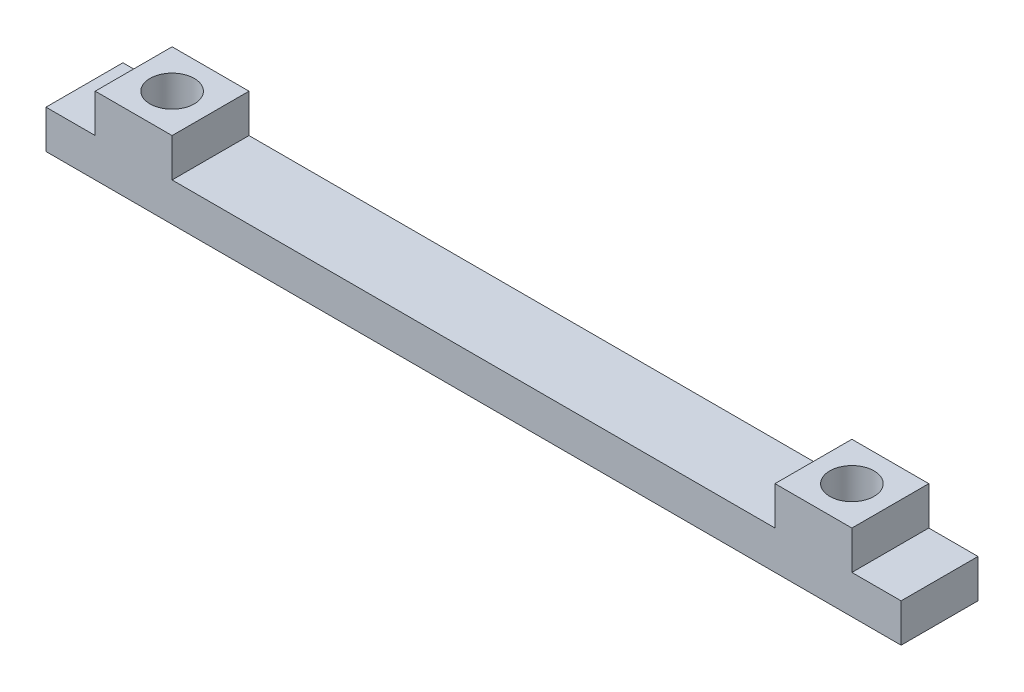
SolidWorks part; units mm, degrees
material "Alloy Steel"
ref_plane "Front Plane" through (0, 0, 0) normal (0, 0, 1) x (1, 0, 0)
ref_plane "Top Plane" through (0, 0, 0) normal (0, 1, 0) x (1, 0, 0)
ref_plane "Right Plane" through (0, 0, 0) normal (1, 0, 0) x (0, 0, -1)
sketch "Sketch1" plane through (0, 0, 0) normal (0, 0, 1) x (1, 0, 0)
  line L0 (35.306, 0) -> (35.306, 3.175) construction
  line L1 (0, 0) -> (70.612, 0)
  line L2 (0, 0) -> (0, 3.175)
  line L3 (0, 3.175) -> (70.612, 3.175)
  line L4 (70.612, 0) -> (70.612, 3.175)
  line L5 (4.064, 3.175) -> (10.414, 3.175)
  line L6 (4.064, 3.175) -> (4.064, 6.35)
  line L7 (4.064, 6.35) -> (10.414, 6.35)
  line L8 (10.414, 3.175) -> (10.414, 6.35)
  line L9 (60.198, 3.175) -> (66.548, 3.175)
  line L10 (60.198, 3.175) -> (60.198, 6.35)
  line L11 (60.198, 6.35) -> (66.548, 6.35)
  line L12 (66.548, 3.175) -> (66.548, 6.35)
  dimension "D1" = 4.064
  dimension "D2" = 3.175
  dimension "D4" = 49.784
  dimension "D5" = 3.175
  dimension "D6" = 6.35
extrude "Boss-Extrude1" add sketch "Sketch1" along normal blind 6.35 contours L1 L0 L3 L2 | L3 L8 L7 L6 | L3 L12 L11 L10 | L0 L1 L4 L3
sketch "Sketch2" plane through (0, 0, 0) normal (0, -1, 0) x (1, 0, 0)
  line L0 (70.612, 3.175) -> (0, 3.175) construction
  line L1 (70.612, 6.35) -> (70.612, 0) construction
  line L2 (0, 6.35) -> (0, 0) construction
  line L3 (7.239, 6.35) -> (7.239, 0) construction
  line L4 (63.373, 6.35) -> (63.373, 0) construction
  line L7 (4.064, 0) -> (10.414, 0)
  line L8 (4.064, 6.35) -> (4.064, 0)
  line L9 (10.414, 6.35) -> (4.064, 6.35)
  line L10 (10.414, 0) -> (10.414, 6.35)
  line L11 (4.064, 0) -> (10.414, 0)
  line L12 (4.064, 6.35) -> (4.064, 0)
  line L13 (10.414, 6.35) -> (4.064, 6.35)
  line L14 (10.414, 0) -> (10.414, 6.35)
  line L15 (60.198, 0) -> (66.548, 0)
  line L16 (60.198, 6.35) -> (60.198, 0)
  line L17 (66.548, 6.35) -> (60.198, 6.35)
  line L18 (66.548, 0) -> (66.548, 6.35)
  line L19 (60.198, 0) -> (66.548, 0)
  line L20 (60.198, 6.35) -> (60.198, 0)
  line L21 (66.548, 6.35) -> (60.198, 6.35)
  line L22 (66.548, 0) -> (66.548, 6.35)
  point P18 (7.239, 3.175)
  point P19 (63.373, 3.175)
  dimension "D1" = 0
  dimension "D2" = 0
hole_wizard "#6 Clearance Hole1" positions "3DSketch1" profile "Sketch4" hole size "#6" standard "ANSI Inch" end condition through all
sketch3d "3DSketch1"
  point P0 (7.239, 0, 3.175)
  point P4 (63.373, 0, 3.175)
sketch "Sketch4" plane through (7.239, 0, 3.175) normal (1, 0, 0) x (0, 0, -1)
  line L0 (0, 0) -> (0, 6.35)
  line L1 (0, 6.35) -> (1.8288, 6.35)
  line L2 (1.8288, 6.35) -> (1.8288, 0)
  line L5 (1.8288, 0) -> (0, 0)
  line L11 (0, -6.35) -> (0, 107.95) construction
  dimension "Thru Hole Dia." = 3.6576
  dimension "Thru Hole Depth" = 6.35
scale "Scale1" [suppressed]
